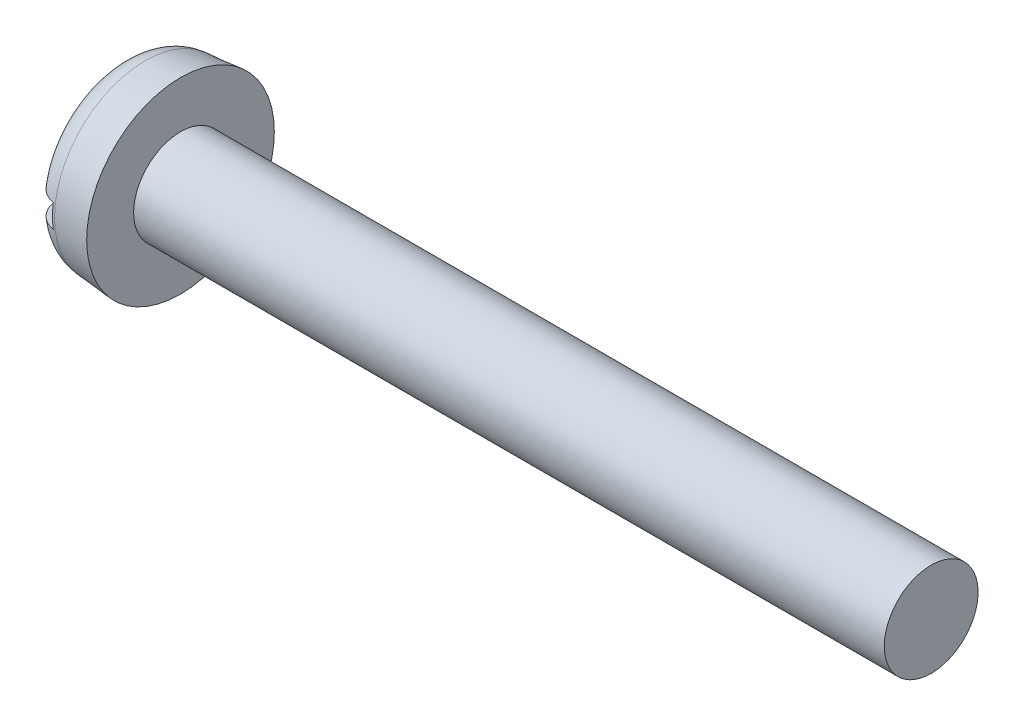
SolidWorks part; units mm, degrees
ref_plane "Plane1" through (0, 0, 0) normal (0, 0, 1) x (1, 0, 0)
ref_plane "Plane2" through (0, 0, 0) normal (0, 1, 0) x (1, 0, 0)
ref_plane "Plane3" through (0, 0, 0) normal (1, 0, 0) x (0, 0, -1)
sketch "BodySke" plane through (0, 0, 0) normal (0, 0, 1) x (1, 0, 0)
  line L0 (1.3, 1) -> (1.3, 2)
  line L1 (0, 0) -> (0, 1.8863)
  line L2 (-25.4, 0) -> (127, 0) construction
  line L3 (17.3, 0) -> (0, 0)
  line L4 (1.3, 1) -> (17.3, 1)
  line L5 (17.3, 1) -> (17.3, 0)
  line L6 (0, 1.8863) -> (1.3, 2)
  line L9 (1.7, 2.5875) -> (1.7, -6.9375) construction
  line L10 (1.3, 6.35) -> (1.3, -3.175) construction
  dimension "Length" = 16
  dimension "Head_ht" = 1.3
  dimension "Advance" = 0.4
  dimension "Thread_nom" = 16
  dimension "Head_dia" = 4
  dimension "Head_side_angle" = 5
  dimension "Diameter" = 2
revolve "Base-Revolve" add sketch "BodySke"
cosmetic thread "ThreadCosmetic" [suppressed]
fillet "Fillet1" [suppressed] radius 0.1
fillet "Fillet2" radius 0.6 1 edges at (0, 0, 1.8863)
sketch "Sketch2" plane through (0, 0, 0) normal (1, 0, 0) x (0, 0, -1)
  line L0 (2, -0.25) -> (-2, -0.25)
  line L1 (2, -0.25) -> (2, 0.25)
  line L2 (-2, 0.25) -> (2, 0.25)
  line L3 (-2, 0.25) -> (-2, -0.25)
  dimension "D1" = 4
  dimension "Slot_width" = 0.5
  dimension "D2" = 2
  dimension "D3" = 0.25
extrude "Slot" cut sketch "Sketch2" along normal blind 0.5
sketch "ThdSchSke" plane through (0, 0, 0) normal (0, 0, 1) x (1, 0, 0)
  line L0 (2.1, -0.774) -> (1.9418, -1)
  line L1 (2.1, -0.774) -> (2.2582, -1)
  line L2 (2.2582, -1) -> (2.2582, -1.25)
  line L3 (-3.175, 0) -> (5.1513, 0) construction
  line L5 (2.2582, -1.25) -> (1.9418, -1.25)
  line L6 (1.9418, -1.25) -> (1.9418, -1)
  dimension "Diameter" = 2
  dimension "SideAngle" = 55
  dimension "VeeAngle" = 70
  dimension "Thread_minor" = 1.548
  dimension "Overcut" = 2.5
  dimension "Start" = 2.1
revolve "ThreadSchematic" [suppressed] cut sketch "ThdSchSke" angle 360 about L3
pattern_linear "ThdSchPat" [suppressed]
equation "\"D1@Sketch2\" = \"Head_dia@BodySke\""
equation "\"D2@Sketch2\" = \"D1@Sketch2\" / 2"
equation "\"D3@Sketch2\" = \"Slot_width@Sketch2\" / 2"
equation "\"Thread_length@ThreadCosmetic\" = ((sgn( (\"Length@BodySke\" - \"Advance@BodySke\" * 2.0 ) - \"Thread_nom@BodySke\" )-1)*( (\"Length@BodySke\" - \"Advance@BodySke\"  * 2.0) - \"Thread_nom@BodySke\" ))/-2+ \"Thread_nom@BodySke\""
equation "\"Thread_minor@ThdSchSke\" = \"Thread_minor@ThreadCosmetic\""
equation "\"Diameter@ThdSchSke\" = \"Diameter@BodySke\""
equation "\"Overcut@ThdSchSke\" = \"Diameter@BodySke\" * 1.25"
equation "\"Start@ThdSchSke\" = \"Head_ht@BodySke\" + \"Length@BodySke\" - \"Thread_length@ThreadCosmetic\"  '---Non-countersunk---"
equation "\"Num_threads@ThdSchPat\" = int( \"Thread_length@ThreadCosmetic\" / \"Advance@BodySke\" + 0.999 )  + 1"
equation "\"Advance@ThdSchPat\" = \"Thread_length@ThreadCosmetic\" /  (\"Num_threads@ThdSchPat\" - 1) 'relax it"
